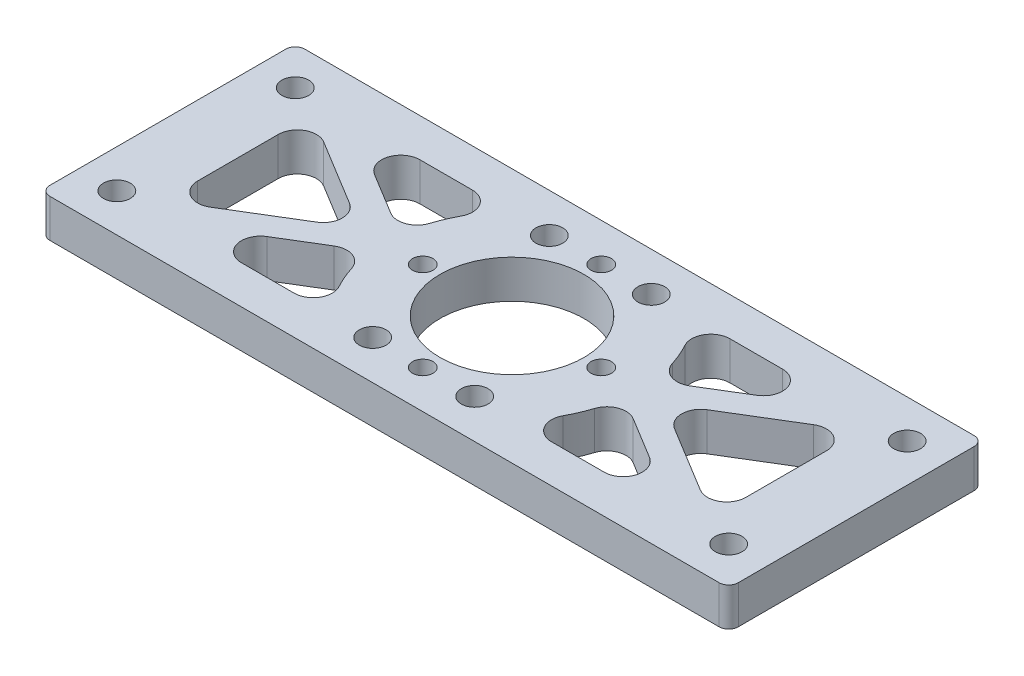
SolidWorks part; units mm, degrees
material "Thornel Mat VMA"
ref_plane "前视基准面" through (0, 0, 0) normal (0, 0, 1) x (1, 0, 0)
ref_plane "上视基准面" through (0, 0, 0) normal (0, 1, 0) x (1, 0, 0)
ref_plane "右视基准面" through (0, 0, 0) normal (1, 0, 0) x (0, 0, -1)
other "Configuration Table"
sketch "草图1" plane through (0, 0, 0) normal (0, 1, 0) x (1, 0, 0)
  line L0 (0, 0) -> (0, 14) construction
  line L1 (-54, -20) -> (54, -20)
  line L2 (-54, -20) -> (-54, 20)
  line L3 (-54, 20) -> (54, 20)
  line L4 (54, -20) -> (54, 20)
  line L5 (-54, -20) -> (54, 20) construction
  line L6 (-54, 20) -> (54, -20) construction
  line L7 (0, 0) -> (8, 13.8564) construction
  line L8 (0, 0) -> (0, -20) construction
  line L9 (0, 0) -> (-54, 0) construction
  circle A0 centre (0, 0) radius 11.3
  circle A1 centre (0, 14) radius 1.6
  circle A2 centre (8, 13.8564) radius 2.1
  circle A3 centre (16, 0) radius 2.1 construction
  circle A4 centre (8, -13.8564) radius 2.1
  circle A5 centre (-8, -13.8564) radius 2.1
  circle A6 centre (-16, 0) radius 2.1 construction
  circle A7 centre (-8, 13.8564) radius 2.1
  circle A8 centre (14, 0) radius 1.6
  circle A9 centre (0, -14) radius 1.6
  circle A10 centre (-14, 0) radius 1.6
  circle A11 centre (-48, -14) radius 2.1
  circle A12 centre (-48, 14) radius 2.1
  circle A13 centre (48, -14) radius 2.1
  circle A14 centre (48, 14) radius 2.1
  point P0 (0, 0)
  point P24 (0, 0)
  point P32 (0, 0)
  dimension "D3" = 14
  dimension "D4" = 3.2
  dimension "D7" = 4.2
  dimension "D8" = 22.6
  dimension "D10" = 4.2
  dimension "D11" = 6
  dimension "D12" = 6
  dimension "D1" = 40
  dimension "D2" = 108
  dimension "D5" = 30
  dimension "D6" = 16
  dimension "D9" = 6
extrude "凸台-拉伸1" add sketch "草图1" along normal mid plane 6
fillet "圆角1" radius 1.5 4 edges at (-54, 0, 20) (-54, 0, -20) (54, 0, -20) (54, 0, 20)
sketch "草图3" plane through (0, 3, 0) normal (0, 1, 0) x (1, 0, 0)
  line L0 (-43, 14) -> (-20, 0) construction
  line L1 (43, -14) -> (-43, -14)
  line L2 (43, -14) -> (43, 14)
  line L3 (43, 14) -> (-43, 14)
  line L4 (-43, -14) -> (-43, 14)
  line L5 (43, -14) -> (-43, 14) construction
  line L6 (43, 14) -> (-43, -14) construction
  line L7 (-20, 0) -> (-43, -14) construction
  line L8 (20, 0) -> (43, 14) construction
  line L9 (20, 0) -> (43, -14) construction
  line L10 (52.5, 20) -> (-52.5, 20) construction
  line L11 (-41.9601, 15.7084) -> (-16.1535, 0)
  line L12 (-16.1535, 0) -> (-41.9601, -15.7084)
  line L13 (16.1535, 0) -> (41.9601, -15.7084)
  line L14 (16.1535, 0) -> (41.9601, 15.7084)
  line L15 (-44.0399, 12.2916) -> (-23.8465, 0)
  line L16 (-23.8465, 0) -> (-44.0399, -12.2916)
  line L17 (23.8465, 0) -> (44.0399, -12.2916)
  line L18 (23.8465, 0) -> (44.0399, 12.2916)
  circle A0 centre (0, 0) radius 20
  circle A1 centre (-48, -14) radius 2.1 construction
  dimension "D1" = 40
  dimension "D2" = 6
  dimension "D3" = 5
  dimension "D4" = 2
  dimension "D5" = 2
extrude "切除-拉伸1" cut sketch "草图3" against normal through all contours A0 L3 L11 | L16 L15 L4 | A0 L12 L1 | A0 L1 L13 | L18 L17 L2 | A0 L14 L3
fillet "圆角2" radius 3 18 edges at (-39.1535, 0, 14) (-19.8715, 0, 2.2632) (-14.2829, 0, 14) (14.2829, 0, 14) (-23.8465, 0, 0) (-43, 0, 11.6586) (43, 0, 11.6586) (23.8465, 0, 0) (43, 0, -11.6586) (39.1535, 0, 14) (19.8715, 0, 2.2632) (39.1535, 0, -14) (19.8715, 0, -2.2632) (14.2829, 0, -14) (-14.2829, 0, -14) (-39.1535, 0, -14) (-19.8715, 0, -2.2632) (-43, 0, -11.6586)
